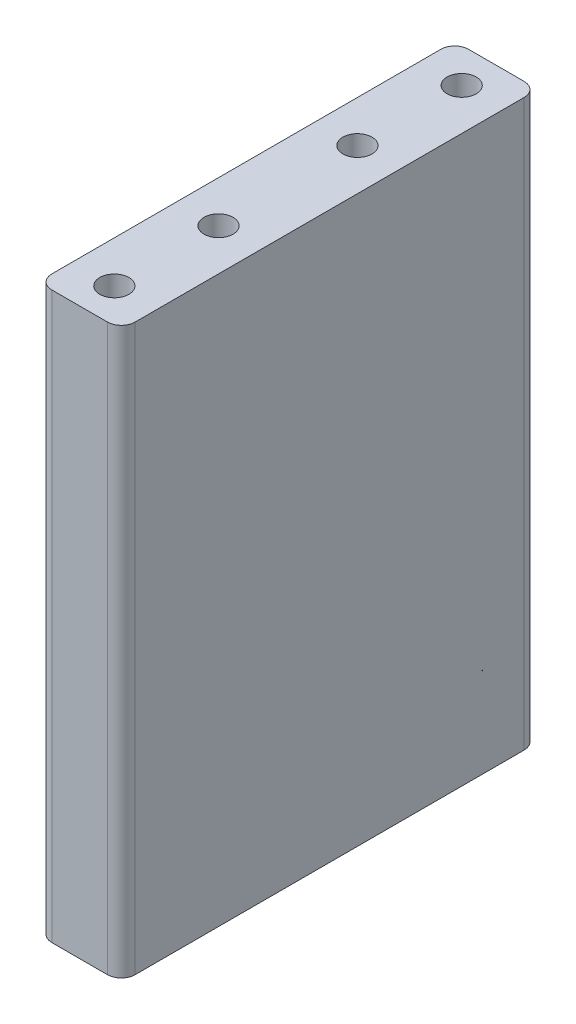
SolidWorks part; units mm, degrees
material "ABS"
ref_plane "Front Plane" through (0, 0, 0) normal (0, 0, 1) x (1, 0, 0)
ref_plane "Top Plane" through (0, 0, 0) normal (0, 1, 0) x (1, 0, 0)
ref_plane "Right Plane" through (0, 0, 0) normal (1, 0, 0) x (0, 0, -1)
sketch "Sketch1" plane through (0, 0, 0) normal (0, 1, 0) x (1, 0, 0)
  line L0 (0, 10) -> (0, -10) construction
  line L1 (-6, 30) -> (6, 30)
  line L2 (-6, 30) -> (-6, -30)
  line L3 (-6, -30) -> (6, -30)
  line L4 (6, 30) -> (6, -30)
  line L5 (0, 25) -> (0, -25) construction
  circle A0 centre (0, 10) radius 2.5 construction
  circle A1 centre (0, -10) radius 2.5 construction
  circle A2 centre (0, 25) radius 2.5 construction
  circle A3 centre (0, -25) radius 2.5 construction
  point P8 (0, 30)
  point P9 (0, 0)
  point P10 (-6, 0)
  point P16 (0, 0)
  dimension "D2" = 5
  dimension "D1" = 20
  dimension "D3" = 12
  dimension "D4" = 60
  dimension "D5" = 50
extrude "Boss-Extrude1" add sketch "Sketch1" against normal blind 81.375 contours L2 L3 L4 L1
hole_wizard "Tap Drill for M5x0.8 Tap1" positions "3DSketch1" profile "Sketch2" hole size "M5x0.8" standard "ANSI Metric" end condition up to next
sketch3d "3DSketch1"
  point P0 (0, 0, -10)
  point P2 (0, 0, 10)
  point P9 (0, 0, -25)
  point P11 (0, 0, 25)
  point P14 (0, 0, -25)
  point P16 (0, 0, 25)
sketch "Sketch2" plane through (0, 0, -10) normal (1, 0, 0) x (0, 0, 1)
  line L0 (0, 0) -> (0, 81.375)
  line L1 (0, 81.375) -> (2.1, 81.375)
  line L2 (2.1, 81.375) -> (2.1, 0)
  line L5 (2.1, 0) -> (0, 0)
  line L11 (0, -6.35) -> (0, 107.95) construction
  dimension "Thru Hole Dia." = 4.2
  dimension "Thru Hole Depth" = 81.375
fillet "Fillet1" radius 2 4 edges at (-6, -40.6875, -30) (6, -40.6875, -30) (-6, -40.6875, 30) (6, -40.6875, 30)
